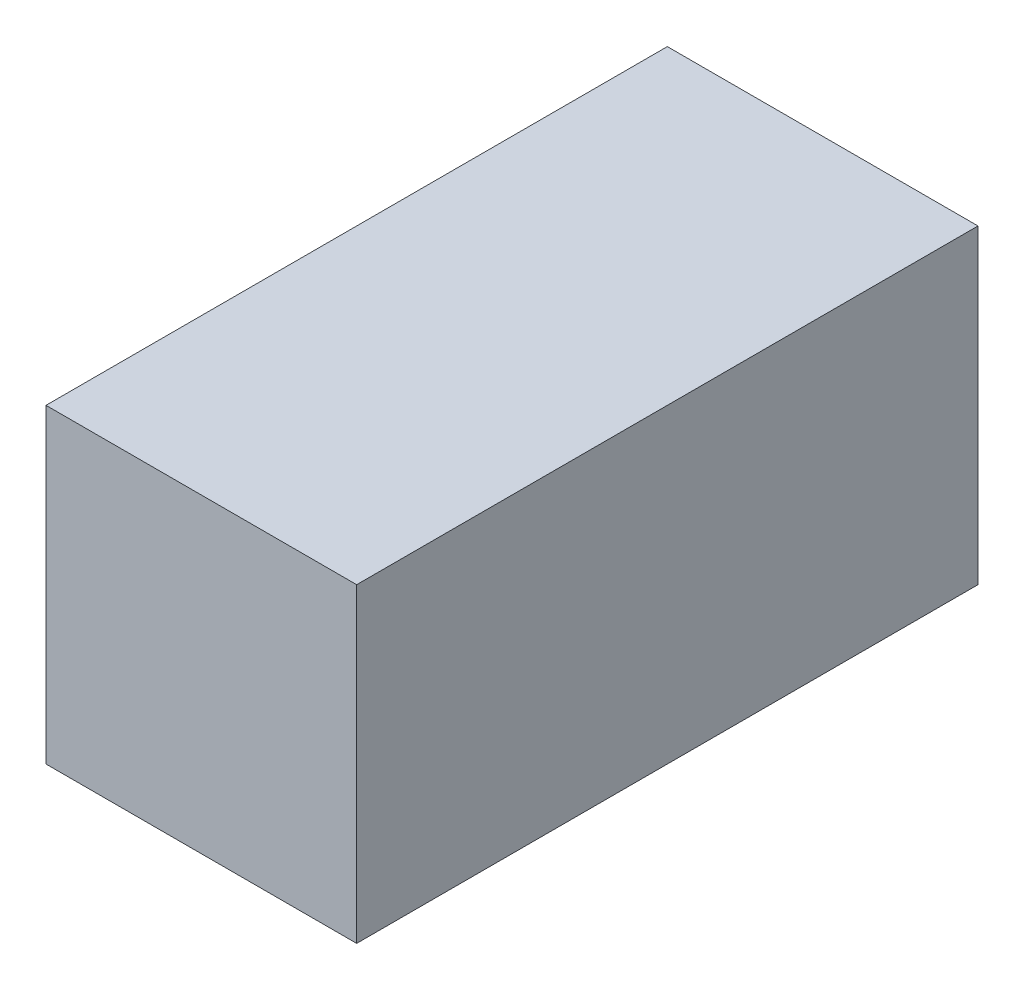
SolidWorks part; units mm, degrees
ref_plane "前视基准面" through (0, 0, 0) normal (0, 0, 1) x (1, 0, 0)
ref_plane "上视基准面" through (0, 0, 0) normal (0, 1, 0) x (1, 0, 0)
ref_plane "右视基准面" through (0, 0, 0) normal (1, 0, 0) x (0, 0, -1)
other "Configuration Table"
sketch "SelectionSeed" plane through (0, 0, 0) normal (0, 0, 1) x (1, 0, 0)
  line L1 (0, 0) -> (10, 0)
  line L2 (0, 0) -> (0, 10)
  line L3 (0, 10) -> (10, 10)
  line L4 (10, 0) -> (10, 10)
  line L6 (5, 5) -> (15, 5)
  line L7 (5, 5) -> (5, 15)
  line L8 (5, 15) -> (15, 15)
  line L9 (15, 5) -> (15, 15)
extrude "SelectionExtrude" add sketch "SelectionSeed" along normal blind 10 contours L7 L6 L4 L3
